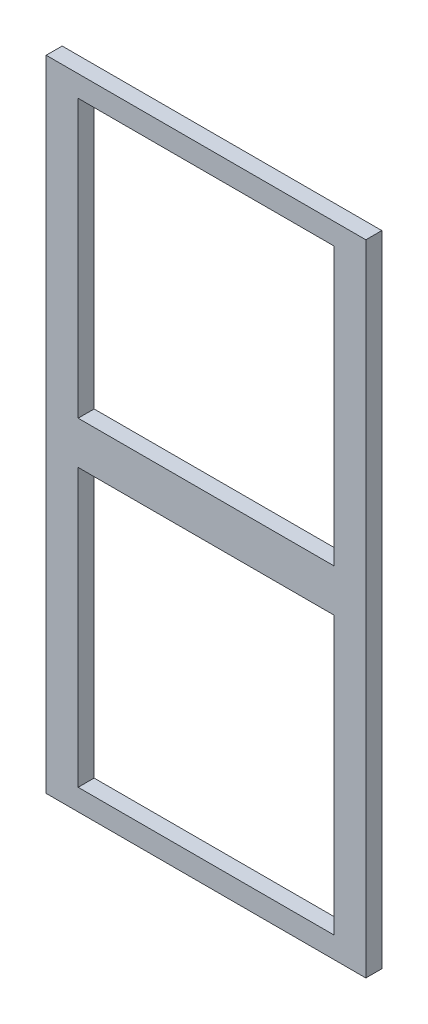
SolidWorks part; units mm, degrees
ref_plane "前基準面" through (0, 0, 0) normal (0, 0, 1) x (1, 0, 0)
ref_plane "上基準面" through (0, 0, 0) normal (0, 1, 0) x (1, 0, 0)
ref_plane "右基準面" through (0, 0, 0) normal (1, 0, 0) x (0, 0, -1)
sketch "草圖1" plane through (0, 0, 0) normal (0, 0, 1) x (1, 0, 0)
  line L1 (-7.5, 15) -> (7.5, 15)
  line L2 (-7.5, 15) -> (-7.5, -15)
  line L3 (-7.5, -15) -> (7.5, -15)
  line L4 (7.5, 15) -> (7.5, -15)
  line L5 (-7.5, 15) -> (7.5, -15) construction
  line L6 (-7.5, -15) -> (7.5, 15) construction
  point P0 (0, 0)
  dimension "D1" = 15
  dimension "D2" = 30
extrude "填料-伸長1" add sketch "草圖1" along normal blind 0.75
sketch "草圖2" plane through (0, 0, 0.75) normal (0, 0, 1) x (1, 0, 0)
  line L0 (-6, 14) -> (6, 14)
  line L1 (-6, -1) -> (6, -1)
  line L2 (-6, -1) -> (-6, -14)
  line L3 (-6, -14) -> (6, -14)
  line L4 (0, 0) -> (0, -15) construction
  line L5 (-7.5, -15) -> (7.5, -15) construction
  line L6 (0, -15) -> (-7.5, 0) construction
  line L7 (-7.5, 15) -> (-7.5, -15) construction
  line L8 (-7.5, 0) -> (0, 0) construction
  line L9 (6, -1) -> (6, -14)
  line L10 (-6, -1) -> (6, -14) construction
  line L11 (-6, -14) -> (6, -1) construction
  line L12 (6, 1) -> (6, 14)
  line L13 (-6, 1) -> (6, 1)
  line L14 (-6, 1) -> (-6, 14)
  point P8 (0, -7.5)
  dimension "D1" = 13
  dimension "D2" = 12
extrude "除料-伸長1" cut sketch "草圖2" against normal blind 0.75
